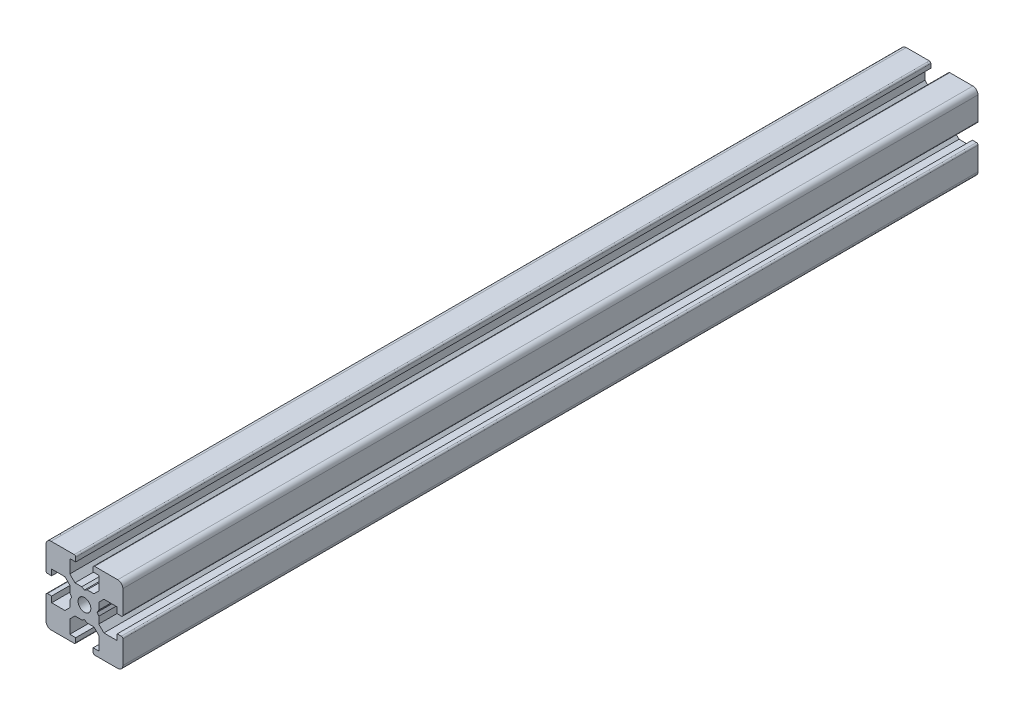
SolidWorks part; units mm, degrees
ref_plane "Front Plane" through (0, 0, 0) normal (0, 0, 1) x (1, 0, 0)
ref_plane "Top Plane" through (0, 0, 0) normal (0, 1, 0) x (1, 0, 0)
ref_plane "Right Plane" through (0, 0, 0) normal (1, 0, 0) x (0, 0, -1)
ref_plane "Plane1" through (0, 0, 300) normal (0, 0, 1) x (1, 0, 0)
sketch "Sketch1" plane through (0, 0, 300) normal (0, 0, 1) x (1, 0, 0)
  line L0 (-7.5, 6.5) -> (-7.5, 2)
  line L1 (-7.2, 1.7) -> (-6.4, 1.7)
  line L2 (-6.4, 1.7) -> (-6.4, 2.85)
  line L3 (-6.4, 2.85) -> (-3.8, 2.85)
  line L4 (-3.8, 2.85) -> (-2.8, 1.85)
  line L5 (-2.8, 1.85) -> (-2.8, 0.5196)
  line L6 (-2.8, 0.5196) -> (-2.5, 0)
  line L7 (-2.5, 0) -> (-2.8, -0.5196)
  line L8 (-2.8, -0.5196) -> (-2.8, -1.85)
  line L9 (-2.8, -1.85) -> (-3.8, -2.85)
  line L10 (-3.8, -2.85) -> (-6.4, -2.85)
  line L11 (-6.4, -2.85) -> (-6.4, -1.7)
  line L12 (-6.4, -1.7) -> (-7.2, -1.7)
  line L13 (-7.5, -2) -> (-7.5, -6.5)
  line L14 (-6.5, -7.5) -> (-2, -7.5)
  line L15 (-1.7, -7.2) -> (-1.7, -6.4)
  line L16 (-1.7, -6.4) -> (-2.85, -6.4)
  line L17 (-2.85, -6.4) -> (-2.85, -3.8)
  line L18 (-2.85, -3.8) -> (-1.85, -2.8)
  line L19 (-1.85, -2.8) -> (-0.5196, -2.8)
  line L20 (-0.5196, -2.8) -> (0, -2.5)
  line L21 (0, -2.5) -> (0.5196, -2.8)
  line L22 (0.5196, -2.8) -> (1.85, -2.8)
  line L23 (1.85, -2.8) -> (2.85, -3.8)
  line L24 (2.85, -3.8) -> (2.85, -6.4)
  line L25 (2.85, -6.4) -> (1.7, -6.4)
  line L26 (1.7, -6.4) -> (1.7, -7.2)
  line L27 (2, -7.5) -> (6.5, -7.5)
  line L28 (7.5, -6.5) -> (7.5, -2)
  line L29 (7.2, -1.7) -> (6.4, -1.7)
  line L30 (6.4, -1.7) -> (6.4, -2.85)
  line L31 (6.4, -2.85) -> (3.8, -2.85)
  line L32 (3.8, -2.85) -> (2.8, -1.85)
  line L33 (2.8, -1.85) -> (2.8, -0.5196)
  line L34 (2.8, -0.5196) -> (2.5, 0)
  line L35 (2.5, 0) -> (2.8, 0.5196)
  line L36 (2.8, 0.5196) -> (2.8, 1.85)
  line L37 (2.8, 1.85) -> (3.8, 2.85)
  line L38 (3.8, 2.85) -> (6.4, 2.85)
  line L39 (6.4, 2.85) -> (6.4, 1.7)
  line L40 (6.4, 1.7) -> (7.2, 1.7)
  line L41 (7.5, 2) -> (7.5, 6.5)
  line L42 (6.5, 7.5) -> (2, 7.5)
  line L43 (1.7, 7.2) -> (1.7, 6.4)
  line L44 (1.7, 6.4) -> (2.85, 6.4)
  line L45 (2.85, 6.4) -> (2.85, 3.8)
  line L46 (2.85, 3.8) -> (1.85, 2.8)
  line L47 (1.85, 2.8) -> (0.5196, 2.8)
  line L48 (0.5196, 2.8) -> (0, 2.5)
  line L49 (0, 2.5) -> (-0.5196, 2.8)
  line L50 (-0.5196, 2.8) -> (-1.85, 2.8)
  line L51 (-1.85, 2.8) -> (-2.85, 3.8)
  line L52 (-2.85, 3.8) -> (-2.85, 6.4)
  line L53 (-2.85, 6.4) -> (-1.7, 6.4)
  line L54 (-1.7, 6.4) -> (-1.7, 7.2)
  line L55 (-2, 7.5) -> (-6.5, 7.5)
  circle A0 centre (0, 0) radius 1.25
  arc A1 (-7.5, 2) -> (-7.2, 1.7) centre (-7.2, 2) ccw
  arc A2 (-7.2, -1.7) -> (-7.5, -2) centre (-7.2, -2) ccw
  arc A3 (-7.5, -6.5) -> (-6.5, -7.5) centre (-6.5, -6.5) ccw
  arc A4 (-2, -7.5) -> (-1.7, -7.2) centre (-2, -7.2) ccw
  arc A5 (1.7, -7.2) -> (2, -7.5) centre (2, -7.2) ccw
  arc A6 (6.5, -7.5) -> (7.5, -6.5) centre (6.5, -6.5) ccw
  arc A7 (7.5, -2) -> (7.2, -1.7) centre (7.2, -2) ccw
  arc A8 (7.2, 1.7) -> (7.5, 2) centre (7.2, 2) ccw
  arc A9 (7.5, 6.5) -> (6.5, 7.5) centre (6.5, 6.5) ccw
  arc A10 (2, 7.5) -> (1.7, 7.2) centre (2, 7.2) ccw
  arc A11 (-1.7, 7.2) -> (-2, 7.5) centre (-2, 7.2) ccw
  arc A12 (-6.5, 7.5) -> (-7.5, 6.5) centre (-6.5, 6.5) ccw
extrude "Boss-Extrude1" add sketch "Sketch1" against normal blind 166.878
